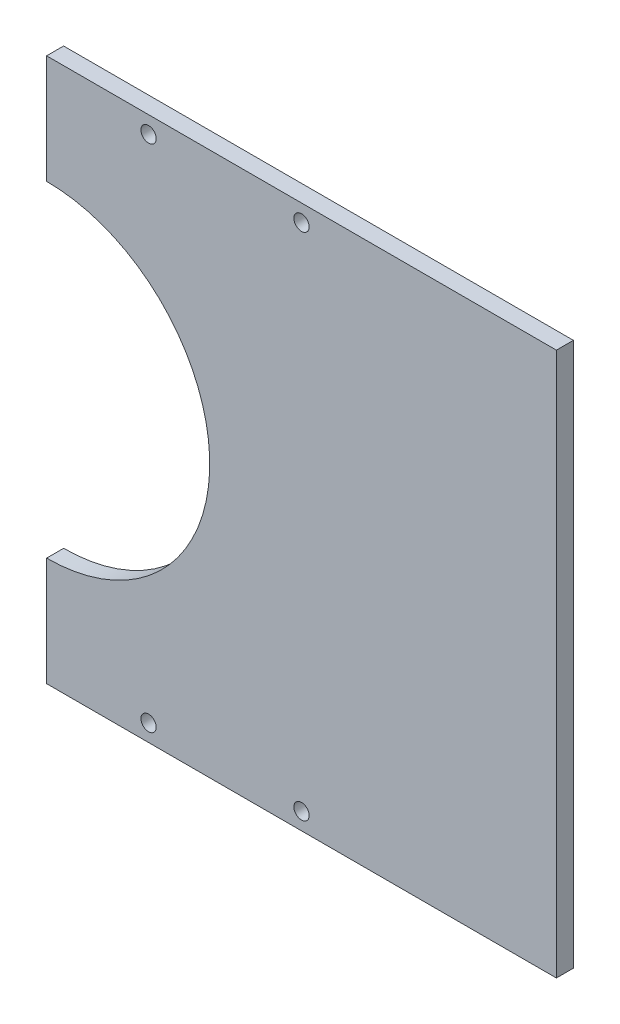
SolidWorks part; units mm, degrees
ref_plane "Front Plane" through (0, 0, 0) normal (1, 0, 0) x (0, 1, 0)
ref_plane "Top Plane" through (0, 0, 0) normal (0, 0, 1) x (0, 1, 0)
ref_plane "Right Plane" through (0, 0, 0) normal (0, 1, 0) x (-1, 0, 0)
sketch "Sketch1" plane through (0, 0, 0) normal (0, 0, 1) x (0, 1, 0)
  line L0 (-48, 75) -> (-80, 75)
  line L1 (80, 75) -> (48, 75)
  line L2 (80, 75) -> (80, -75)
  line L3 (80, -75) -> (-80, -75)
  line L4 (-80, 75) -> (-80, -75)
  line L5 (80, 75) -> (-80, -75) construction
  line L6 (80, -75) -> (-80, 75) construction
  arc A0 (-48, 75) -> (48, 75) centre (0, 75) ccw
  point P0 (0, 0)
  dimension "D4" = 96
  dimension "D1" = 160
  dimension "D2" = 150
extrude "Boss-Extrude1" add sketch "Sketch1" along normal blind 5
sketch "Sketch2" plane through (0, 0, 5) normal (0, 0, 1) x (1, 0, 0)
  line L0 (2.75, 0) -> (-2.75, 0) construction
  line L1 (-75, -80) -> (75, -80) construction
  circle A0 centre (0, -75) radius 2.25
  circle A1 centre (-45, -75) radius 2.25
  circle A2 centre (0, 75) radius 2.25
  circle A3 centre (-45, 75) radius 2.25
  point P4 (0, 0)
  point P5 (0, -80)
  point P8 (-32.3841, -72.377)
  point P9 (0, 0)
  dimension "D1" = 4.5
  dimension "D2" = 5
  dimension "D3" = 45
extrude "Cut-Extrude1" cut sketch "Sketch2" against normal through all both and the other way through all
